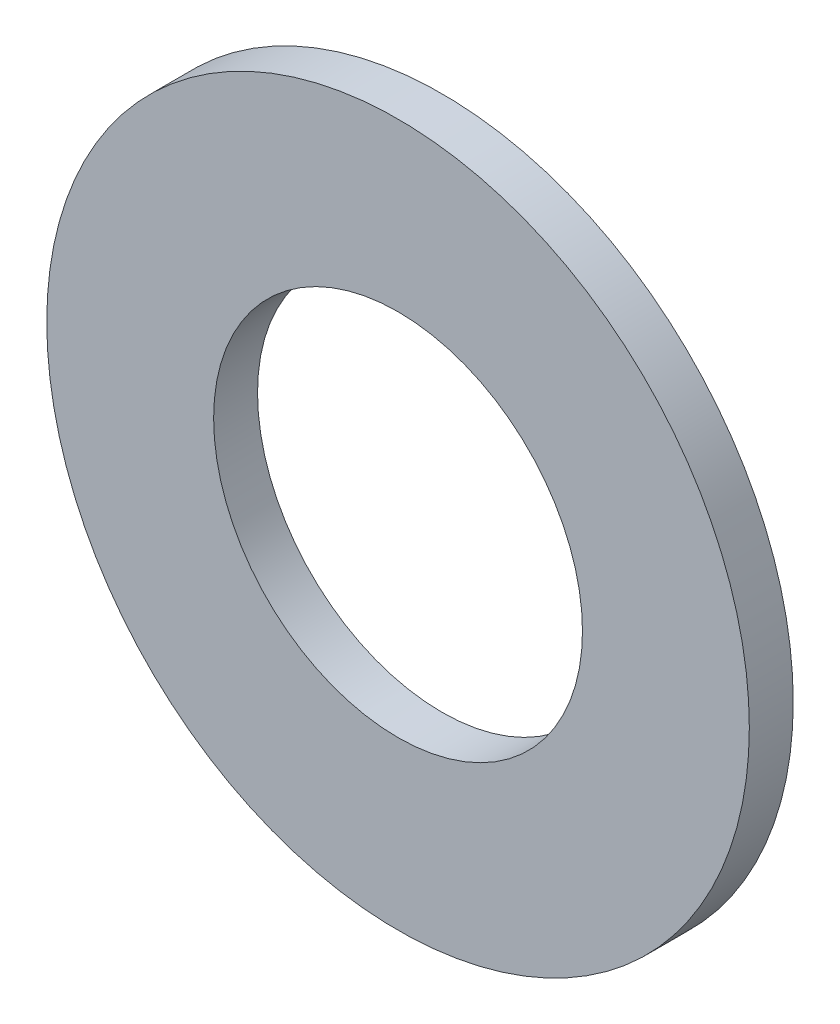
SolidWorks part; units mm, degrees
ref_plane "Front Plane" through (0, 0, 0) normal (0, 0, 1) x (1, 0, 0)
ref_plane "Top Plane" through (0, 0, 0) normal (0, 1, 0) x (1, 0, 0)
ref_plane "Right Plane" through (0, 0, 0) normal (1, 0, 0) x (0, 0, -1)
sketch "Washer_profile" plane through (0, 0, 0) normal (0, 0, 1) x (1, 0, 0)
  circle A0 centre (0, 0) radius 4
  circle A1 centre (0, 0) radius 2.1
  dimension "D1" = 8
  dimension "D2" = 4.2
extrude "Washer" add sketch "Washer_profile" along normal blind 0.5
